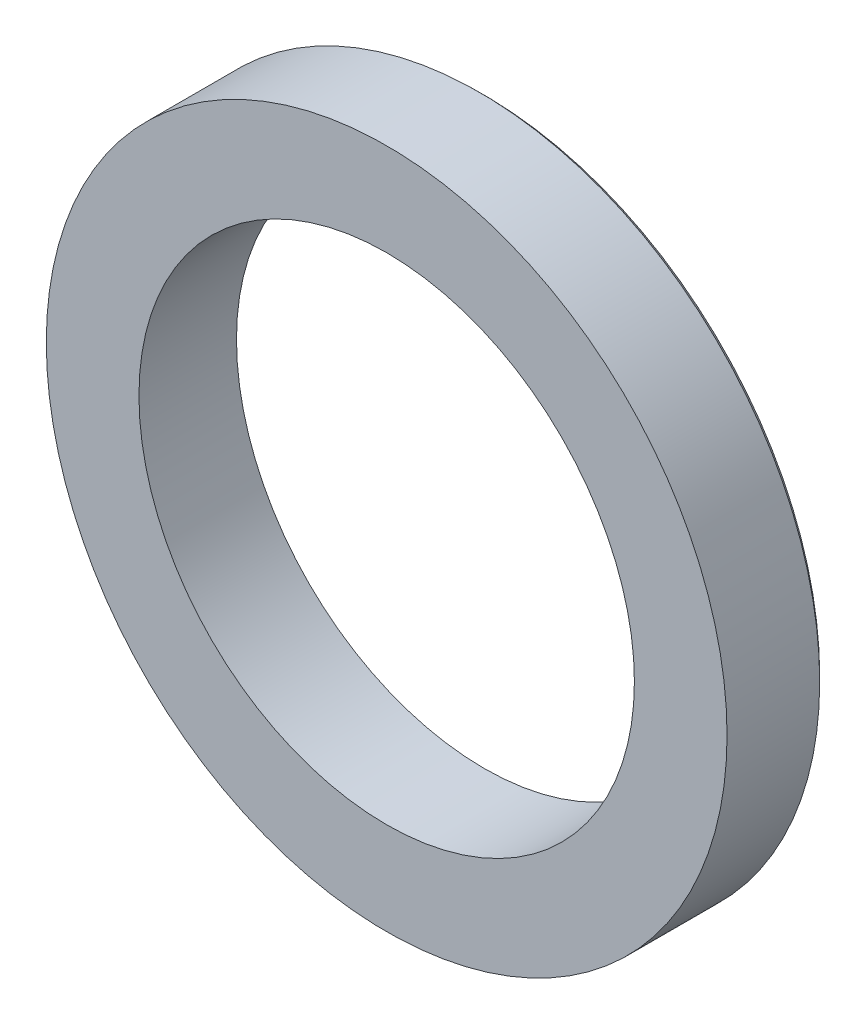
SolidWorks part; units mm, degrees
ref_plane "Front Plane" through (0, 0, 0) normal (0, 0, 1) x (1, 0, 0)
ref_plane "Top Plane" through (0, 0, 0) normal (0, 1, 0) x (1, 0, 0)
ref_plane "Right Plane" through (0, 0, 0) normal (1, 0, 0) x (0, 0, -1)
sketch "Sketch1" plane through (0, 0, 0) normal (0, 0, 1) x (1, 0, 0)
  circle A0 centre (0, 0) radius 17.45
  dimension "D1" = 34.9
extrude "Boss-Extrude1" add sketch "Sketch1" along normal blind 5
sketch "Sketch2" plane through (0, 0, 0) normal (0, 0, -1) x (-1, 0, 0)
  circle A0 centre (0, 0) radius 12.65
  dimension "D1" = 25.3
extrude "Boss-Extrude2" add sketch "Sketch2" along normal blind 6.3
sketch "Sketch3" plane through (0, 0, 5) normal (0, 0, 1) x (1, 0, 0)
  circle A0 centre (0, 0) radius 12.7
  dimension "D1" = 25.4
extrude "Cut-Extrude1" cut sketch "Sketch3" against normal through all
chamfer "Chamfer3" distance 0.25 angle 45 1 edges at (17.45, 0, 0)
